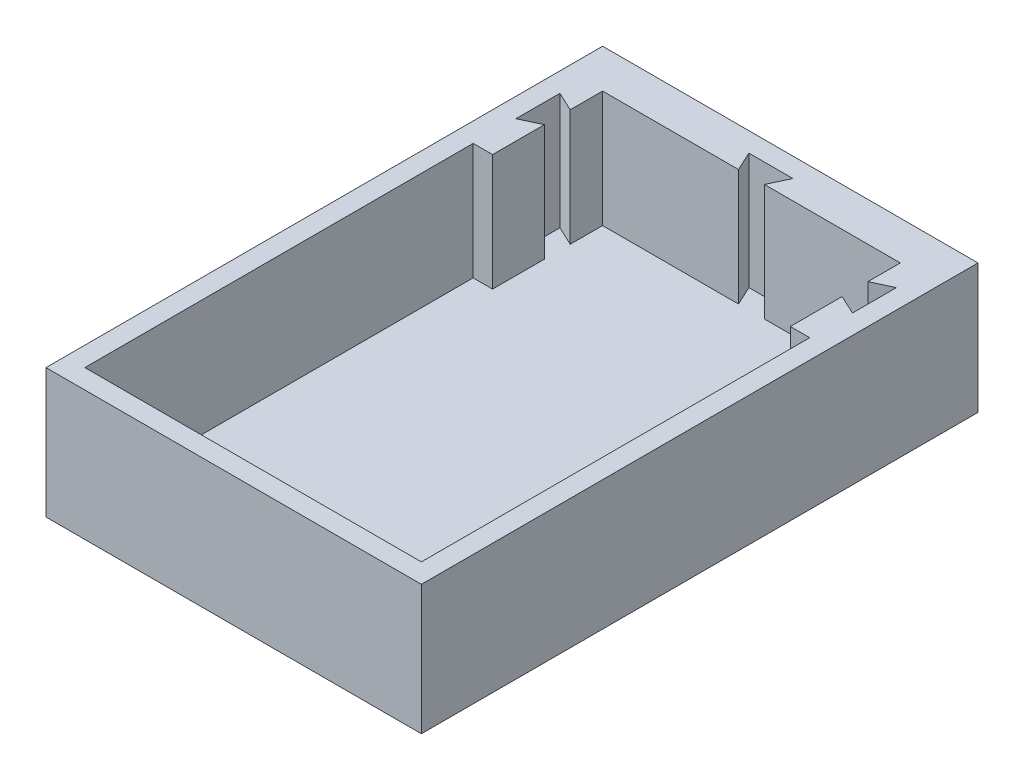
SolidWorks part; units mm, degrees
ref_plane "Front Plane" through (0, 0, 0) normal (0, 0, 1) x (1, 0, 0)
ref_plane "Top Plane" through (0, 0, 0) normal (0, 1, 0) x (1, 0, 0)
ref_plane "Right Plane" through (0, 0, 0) normal (1, 0, 0) x (0, 0, -1)
sketch "Sketch1" plane through (0, 0, 0) normal (0, 1, 0) x (1, 0, 0)
  line L1 (0, 0) -> (66.04, 0)
  line L2 (0, 0) -> (0, 101.6)
  line L3 (0, 101.6) -> (66.04, 101.6)
  line L4 (66.04, 0) -> (66.04, 101.6)
  dimension "D1" = 101.6
  dimension "D2" = 66.04
extrude "Base Extrude" add sketch "Sketch1" along normal blind 2.54
sketch "Sketch2" plane through (0, 0, 0) normal (0, -1, 0) x (1, 0, 0)
  line L1 (0, 0) -> (66.04, 0)
  line L2 (0, 0) -> (0, -101.6)
  line L3 (0, -101.6) -> (66.04, -101.6)
  line L4 (66.04, 0) -> (66.04, -101.6)
  line L5 (-3.81, 3.81) -> (69.85, 3.81)
  line L6 (-3.81, 3.81) -> (-3.81, -105.41)
  line L7 (-3.81, -105.41) -> (69.85, -105.41)
  line L8 (69.85, 3.81) -> (69.85, -105.41)
  dimension "D1" = 3.81
  dimension "D2" = 3.81
  dimension "D3" = 3.81
  dimension "D4" = 3.81
extrude "Walls" add sketch "Sketch2" against normal blind 25.4
sketch "Sketch3" plane through (0, 25.4, 0) normal (0, 1, 0) x (1, 0, 0)
  line L0 (66.04, 101.6) -> (66.04, 0) construction
  line L1 (0, 101.6) -> (66.04, 101.6)
  line L2 (0, 101.6) -> (0, 76.2)
  line L3 (0, 76.2) -> (3.81, 76.2)
  line L4 (66.04, 101.6) -> (66.04, 76.2)
  line L5 (0, 93.2166) -> (3.81, 91.44)
  line L6 (3.81, 76.2) -> (3.81, 86.36)
  line L7 (3.81, 86.36) -> (0, 84.5834)
  line L8 (0, 101.6) -> (0, 0) construction
  line L9 (3.81, 91.44) -> (3.81, 97.79)
  line L10 (3.81, 97.79) -> (30.48, 97.79)
  line L11 (30.48, 97.79) -> (28.7034, 101.6)
  line L12 (28.7034, 101.6) -> (37.3366, 101.6)
  line L13 (37.3366, 101.6) -> (35.56, 97.79)
  line L14 (35.56, 97.79) -> (62.23, 97.79)
  line L15 (62.23, 97.79) -> (62.23, 91.44)
  line L16 (62.23, 91.44) -> (66.04, 93.2166)
  line L17 (66.04, 93.2166) -> (66.04, 84.5834)
  line L18 (66.04, 84.5834) -> (62.23, 86.36)
  line L19 (62.23, 86.36) -> (62.23, 76.2)
  line L20 (62.23, 76.2) -> (66.04, 76.2)
  line L21 (66.04, 0) -> (66.04, 101.6) construction
  line L22 (3.81, 91.44) -> (3.81, 86.36) construction
  line L23 (30.48, 97.79) -> (35.56, 97.79) construction
  point P11 (3.81, 88.9)
  point P26 (33.02, 97.79)
  point P31 (33.02, 101.6)
  line M17 (0, 0) -> (0, 101.6)
  line M18 (0, 101.6) -> (66.04, 101.6)
  line M19 (66.04, 101.6) -> (66.04, 0)
  dimension "D1" = 115
  dimension "D2" = 3.81
  dimension "D3" = 25.4
  dimension "D4" = 12.7
  dimension "D5" = 5.08
  dimension "D6" = 5.08
  dimension "D7" = 3.81
extrude "Button Guide" add sketch "Sketch3" against normal up to surface (22.86 mm away) contours L6 L7 L3 M17 | L10 L11 L2 L5 L9 M18 | L15 L16 L13 L14 M19 M18 | L19 L20 L18 M19 up to face at (33.02, 2.54, -50.8)
